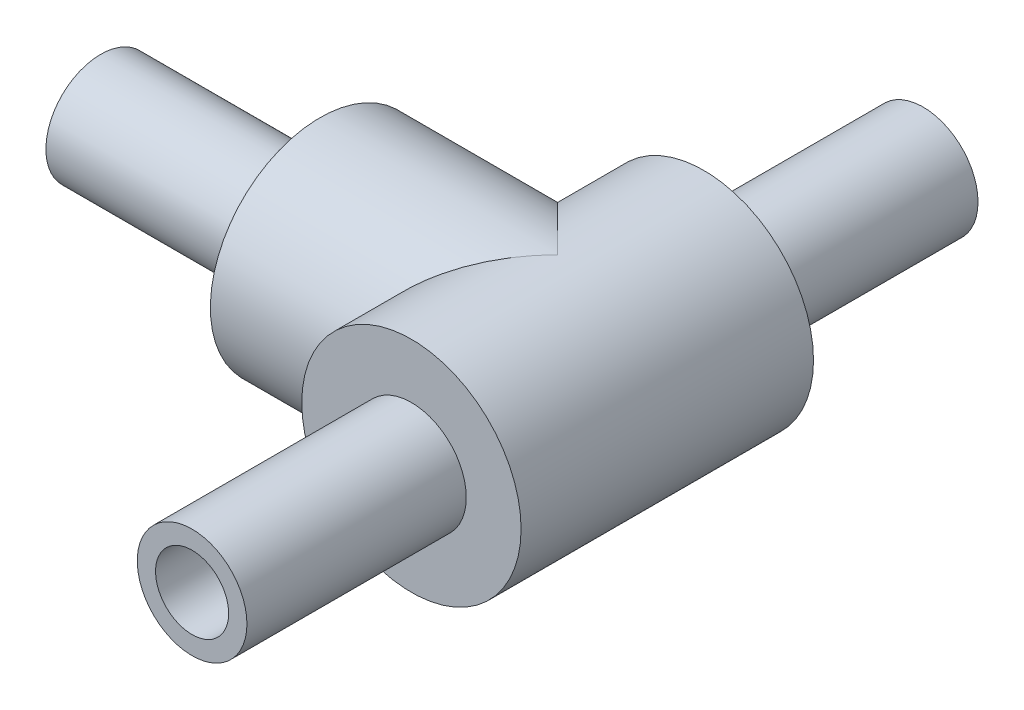
SolidWorks part; units mm, degrees
material "PP Copolymer"
ref_plane "Front Plane" through (0, 0, 0) normal (0, 0, 1) x (1, 0, 0)
ref_plane "Top Plane" through (0, 0, 0) normal (0, 1, 0) x (1, 0, 0)
ref_plane "Right Plane" through (0, 0, 0) normal (1, 0, 0) x (0, 0, -1)
other "Configuration Table"
sketch "Sketch1" plane through (0, 0, 0) normal (0, 0, 1) x (1, 0, 0)
  circle A0 centre (0, 0) radius 6
  dimension "D1" = 12
extrude "Run_Hub" add sketch "Sketch1" along normal blind 16 from offset 8
sketch "Sketch2" plane through (0, 0, 0) normal (1, 0, 0) x (0, 0, -1)
  circle A0 centre (0, 0) radius 6
  dimension "D1" = 12
extrude "Branch_Hub" add sketch "Sketch2" along normal blind 13 from offset 13
sketch "Sketch3" plane through (0, 0, 0) normal (0, 0, 1) x (1, 0, 0)
  circle A0 centre (0, 0) radius 3
  dimension "D1" = 6
extrude "Barb_Front" add sketch "Sketch3" along normal blind 12 from offset 8
sketch "Sketch4" plane through (0, 0, 0) normal (0, 0, 1) x (1, 0, 0)
  circle A0 centre (0, 0) radius 3
  dimension "D1" = 6
extrude "Barb_Back" add sketch "Sketch4" along normal blind 12 from offset 20
sketch "Sketch5" plane through (0, 0, 0) normal (1, 0, 0) x (0, 0, -1)
  circle A0 centre (0, 0) radius 3
  dimension "D1" = 6
extrude "Barb_Branch" add sketch "Sketch5" along normal blind 12 from offset 25
sketch "Sketch6" plane through (0, 0, 0) normal (0, 0, 1) x (1, 0, 0)
  circle A0 centre (0, 0) radius 2
  dimension "D1" = 4
extrude "Run_Bore" cut sketch "Sketch6" along normal through all and the other way through all
sketch "Sketch7" plane through (0, 0, 0) normal (1, 0, 0) x (0, 0, -1)
  circle A0 centre (0, 0) radius 2
  dimension "D1" = 4
extrude "Branch_Bore" cut sketch "Sketch7" along normal blind 26 from offset 26
equation "\"Jar_OD\"= 90  'ASSUMED - Part G fallback - jar outer diameter"
equation "\"Jar_H\"= 120  'ASSUMED - Part G fallback - jar height"
equation "\"Pump_L\"= 45  'ASSUMED - Part G fallback"
equation "\"Pump_W\"= 24  'ASSUMED - Part G fallback"
equation "\"Pump_H\"= 33  'ASSUMED - Part G fallback"
equation "\"Pump_Outlet_OD\"= 7.5  'ASSUMED - Part G fallback"
equation "\"Tube_OD\"= 8  'ASSUMED - Part G fallback"
equation "\"Tube_ID\"= 6  'ASSUMED - Part G fallback"
equation "\"TDS_Body_Dia\"= 12  'ASSUMED - Part G fallback"
equation "\"TDS_Wet_Len\"= 45  'ASSUMED - Part G fallback - length in water"
equation "\"DS_Tube_Dia\"= 6  'ASSUMED - Part G fallback"
equation "\"DS_Tube_Len\"= 50  'ASSUMED - Part G fallback"
equation "\"ORP_Body_Dia\"= 12  'ASSUMED - Part G fallback"
equation "\"ORP_Body_Len\"= 150  'ASSUMED - Part G fallback"
equation "\"ORP_Cap_Dia\"= 16  'ASSUMED - Part G fallback"
equation "\"Turb_W\"= 33  'ASSUMED - Part G fallback - head width"
equation "\"Turb_D\"= 28  'ASSUMED - Part G fallback - head depth"
equation "\"Turb_H\"= 30  'ASSUMED - Part G fallback - head height"
equation "\"Turb_Slot_W\"= 10  'ASSUMED - Part G fallback - slot width"
equation "\"Flow_L\"= 62  'ASSUMED - Part G fallback YF-S201"
equation "\"Flow_W\"= 36  'ASSUMED - Part G fallback"
equation "\"Flow_H\"= 35  'ASSUMED - Part G fallback"
equation "\"Thread_G12_OD\"= 20.955  'ASSUMED - Part G fallback thread G1/2 (major diameter)"
equation "\"Valve_L\"= 75  'ASSUMED - Part G fallback"
equation "\"Valve_W\"= 45  'ASSUMED - Part G fallback"
equation "\"Valve_H\"= 60  'ASSUMED - Part G fallback"
equation "\"Tee_L\"= 40  'ASSUMED - Part G fallback - overall length"
equation "\"Tee_Branch_L\"= 25  'ASSUMED - Part G fallback"
equation "\"Tee_OD\"= 12  'ASSUMED - Part G fallback"
equation "\"Cuv_W\"= 12.5  'ASSUMED - old R3 cuvette (station suppressed in SS4)"
equation "\"Cuv_D\"= 12.5  'ASSUMED - old R3 cuvette (station suppressed in SS4)"
equation "\"Cuv_H\"= 45  'ASSUMED - old R3 cuvette (station suppressed in SS4)"
equation "\"LED_Board_L\"= 20  'ASSUMED - Part G fallback"
equation "\"LED_Board_W\"= 20  'ASSUMED - Part G fallback - LED at centre"
equation "\"GUVA_L\"= 20  'ASSUMED - Part G fallback"
equation "\"GUVA_W\"= 12  'ASSUMED - Part G fallback - sensor at centre"
equation "\"Reed_L\"= 27  'ASSUMED - Part G fallback MC-38 half"
equation "\"Reed_W\"= 14  'ASSUMED - Part G fallback"
equation "\"Reed_H\"= 8  'ASSUMED - Part G fallback"
equation "\"ESP_L\"= 51  'ASSUMED - Part G fallback"
equation "\"ESP_W\"= 28  'ASSUMED - Part G fallback"
equation "\"TFT_L\"= 58  'ASSUMED - Part G fallback - board"
equation "\"TFT_W\"= 35  'ASSUMED - Part G fallback - board"
equation "\"TFT_Win_L\"= 35  'ASSUMED - Part G fallback - visible window"
equation "\"TFT_Win_W\"= 28  'ASSUMED - Part G fallback - visible window"
equation "\"Relay_L\"= 50  'ASSUMED - Part G fallback"
equation "\"Relay_W\"= 26  'ASSUMED - Part G fallback"
equation "\"Relay_H\"= 19  'ASSUMED - Part G fallback"
equation "\"Mosfet_L\"= 34  'ASSUMED - Part G fallback"
equation "\"Mosfet_W\"= 17  'ASSUMED - Part G fallback"
equation "\"Mosfet_H\"= 12  'ASSUMED - Part G fallback"
equation "\"TDS_Board_L\"= 42  'ASSUMED - Part G fallback"
equation "\"TDS_Board_W\"= 32  'ASSUMED - Part G fallback"
equation "\"Turb_Board_L\"= 38  'ASSUMED - Part G fallback"
equation "\"Turb_Board_W\"= 28  'ASSUMED - Part G fallback"
equation "\"BNC_Thread_Dia\"= 9.5  'ASSUMED - Part G fallback"
equation "\"Plate_L\"= 420  'ASSUMED - Part G fallback"
equation "\"Plate_W\"= 297  'ASSUMED - Part G fallback"
equation "\"Plate_T\"= 6  'ASSUMED - Part G fallback"
equation "\"Probe_Clr\"= 0.3  'DESIGN VALUE - Part C rule 3 - printed probe hole = diameter + 0.3"
equation "\"Cuv_Clr\"= 0.2  'DESIGN VALUE - Part C rule 3 - cuvette pocket = size + 0.2"
equation "\"Label_H\"= 0.6  'DESIGN VALUE - Part D - raised label height"
equation "\"D1@Sketch1\" = \"Tee_OD\""
equation "\"D1@Sketch3\" = \"Tube_ID\""
equation "\"Booster_L\"= 150  'ASSUMED - Part G fallback - booster pump"
equation "\"Booster_W\"= 95  'ASSUMED - Part G fallback"
equation "\"Booster_H\"= 100  'ASSUMED - Part G fallback"
equation "\"PTube_OD\"= 6.35  'ASSUMED - Part G fallback - product tube 1/4 inch"
equation "\"Qz_Out\"= 12  'ASSUMED - Part G fallback - quartz channel outside square"
equation "\"Qz_Path\"= 10  'ASSUMED - Part G fallback - quartz channel inside light path"
equation "\"Qz_L\"= 40  'ASSUMED - Part G fallback - quartz channel length"
equation "\"LED860_Dia\"= 5  'ASSUMED - Part G fallback - 860 nm LED"
equation "\"BPW_L\"= 5.4  'ASSUMED - Part G fallback - BPW34"
equation "\"BPW_W\"= 4.3  'ASSUMED - Part G fallback - BPW34"
equation "\"Cart_Dia\"= 50  'ASSUMED - Part G fallback - sediment and pre-carbon cartridges"
equation "\"Cart_L\"= 255  'ASSUMED - Part G fallback"
equation "\"UF_Dia\"= 50  'ASSUMED - Part G fallback - UF cartridge"
equation "\"UF_L\"= 260  'ASSUMED - Part G fallback"
equation "\"RO_Dia\"= 62  'ASSUMED - Part G fallback - RO membrane housing"
equation "\"RO_L\"= 300  'ASSUMED - Part G fallback"
equation "\"UVC_Dia\"= 40  'ASSUMED - Part G fallback - UV-C chamber"
equation "\"UVC_L\"= 300  'ASSUMED - Part G fallback"
equation "\"Tank_W\"= 260  'ASSUMED - Part G fallback - storage tank"
equation "\"Tank_D\"= 160  'ASSUMED - Part G fallback"
equation "\"Tank_H\"= 300  'ASSUMED - Part G fallback"
equation "\"Cab_W\"= 400  'ASSUMED - Part G fallback - purifier cabinet"
equation "\"Cab_D\"= 270  'ASSUMED - Part G fallback"
equation "\"Cab_H\"= 560  'ASSUMED - Part G fallback"
equation "\"ORP_Board_L\"= 40  'ASSUMED - Part G fallback - ORP buffer board"
equation "\"ORP_Board_W\"= 30  'ASSUMED - Part G fallback"
equation "\"Opt_Board_L\"= 50  'ASSUMED - Part G fallback - optical front-end board"
equation "\"Opt_Board_W\"= 40  'ASSUMED - Part G fallback"
equation "\"Buck_L\"= 43  'ASSUMED - Part G fallback - 12 V to 5 V buck module"
equation "\"Buck_W\"= 21  'ASSUMED - Part G fallback"
equation "\"Buck_H\"= 14  'ASSUMED - Part G fallback"
equation "\"BB_L\"= 165  'ASSUMED - Part G fallback - breadboard (As_Built_R3 only)"
equation "\"BB_W\"= 55  'ASSUMED - Part G fallback"
equation "\"BB_H\"= 10  'ASSUMED - Part G fallback"
